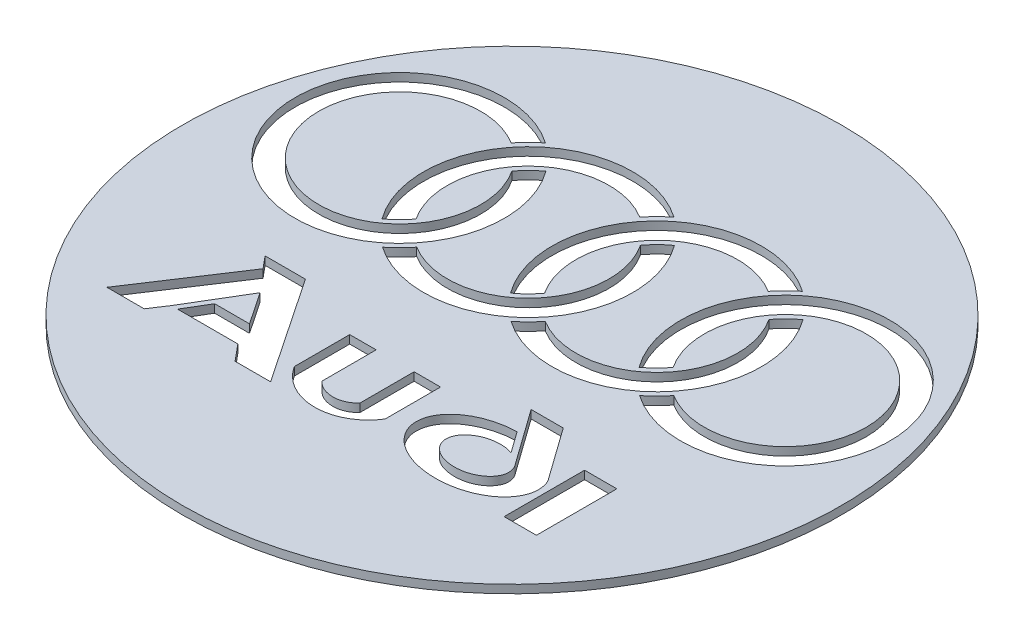
SolidWorks part; units mm, degrees
ref_plane "Front Plane" through (0, 0, 0) normal (0, 0, 1) x (1, 0, 0)
ref_plane "Top Plane" through (0, 0, 0) normal (0, 1, 0) x (1, 0, 0)
ref_plane "Right Plane" through (0, 0, 0) normal (1, 0, 0) x (0, 0, -1)
sketch "Sketch1" plane through (0, 0, 0) normal (0, 1, 0) x (1, 0, 0)
  circle A0 centre (0, 0) radius 127
  dimension "D1" = 254
extrude "Boss-Extrude1" add sketch "Sketch1" along normal blind 3.175
sketch "Sketch2" plane through (0, 3.175, 0) normal (0, 1, 0) x (1, 0, 0)
  line L0 (-62.6808, 3.9651) -> (137.3192, 3.9651) construction
  line L1 (-67.3927, -27.7613) -> (-63.4978, -32.4496)
  line L2 (-63.4978, -32.4496) -> (-87.3925, -68.7244)
  line L3 (-87.3925, -68.7244) -> (-73.0256, -68.7244)
  line L4 (-73.0256, -68.7244) -> (-68.8589, -62.399)
  line L5 (-66.4907, -62.399) -> (-43.2468, -62.399)
  line L6 (-43.2468, -62.399) -> (-37.9919, -68.7244)
  line L7 (-37.9919, -68.7244) -> (-24.3085, -68.7244)
  line L8 (-24.3085, -68.7244) -> (-51.8466, -27.7613)
  line L9 (-51.8466, -27.7613) -> (-67.3927, -27.7613)
  line L10 (-63.4978, -53.4431) -> (-56.0529, -41.0353)
  line L11 (-56.0529, -41.0353) -> (-47.7115, -53.4431)
  line L12 (-47.7115, -53.4431) -> (-61.1295, -53.4431)
  line L13 (35.1296, -27.7613) -> (47.5132, -27.7613)
  line L14 (47.5132, -27.7613) -> (62.2282, -48.3786)
  line L15 (35.1296, -27.7613) -> (50.6169, -49.4607)
  line L16 (-24.8134, -37.7244) -> (-14.6292, -37.7244)
  line L17 (65.691, -37.7244) -> (78.1298, -37.7244)
  line L18 (65.691, -37.7244) -> (65.691, -68.7244)
  line L19 (65.691, -68.7244) -> (78.1298, -68.7244)
  line L20 (78.1298, -37.7244) -> (78.1298, -68.7244)
  line L21 (10.1842, -37.7244) -> (10.1842, -59.0745)
  line L22 (0, -37.7244) -> (0, -58.6653)
  line L23 (-14.6292, -37.7244) -> (-14.6292, -58.6653)
  line L24 (-24.8134, -37.7244) -> (-24.8134, -59.0745)
  line L25 (0, -37.7244) -> (10.1842, -37.7244)
  line L26 (-68.8589, -62.399) -> (-63.4978, -53.4431)
  line L27 (-66.4907, -62.399) -> (-61.1295, -53.4431)
  line L28 (-67.1155, -63.4427) -> (-61.7543, -54.4868) construction
  line L31 (39.8509, -37.8742) -> (45.6791, -46.0402)
  line L32 (-24.3085, -68.7244) -> (84.4236, -68.7244) construction
  arc A0 (-24.8134, -59.0745) -> (10.1842, -59.0745) centre (-7.3146, -48.0336) ccw
  arc A1 (-14.6292, -58.6653) -> (0, -58.6653) centre (-7.3146, -51.6147) ccw
  arc A2 (-51.0647, 63.9504) -> (-42.7697, 5.4957) centre (-74.1332, 30.861) ccw
  arc A3 (-57.6633, 57.3592) -> (-49.3682, 11.8844) centre (-74.1332, 30.861) ccw
  arc A4 (-42.7697, 56.2262) -> (-50.6065, 13.6202) centre (-24.6032, 30.861) ccw
  arc A5 (-49.3682, 62.7006) -> (-57.205, 7.1083) centre (-24.6032, 30.861) ccw
  arc A6 (6.7603, 56.2262) -> (-1.0765, 13.6202) centre (24.9268, 30.861) ccw
  arc A7 (0.1618, 62.7006) -> (-7.675, 7.1083) centre (24.9268, 30.861) ccw
  arc A8 (56.2903, 56.2262) -> (48.4535, 13.6202) centre (74.4568, 30.861) ccw
  arc A9 (49.6918, 62.7006) -> (41.855, 7.1083) centre (74.4568, 30.861) ccw
  arc A10 (-41.0732, 4.3627) -> (0.1618, 11.8844) centre (-24.6032, 30.861) ccw
  arc A11 (-47.6717, -2.2285) -> (6.7603, 5.4957) centre (-24.6032, 30.861) ccw
  arc A12 (-49.3682, 11.8844) -> (-48.1299, 48.1017) centre (-74.1332, 30.861) ccw
  arc A13 (-42.7697, 5.4957) -> (-41.5314, 54.6136) centre (-74.1332, 30.861) ccw
  arc A14 (-1.5347, 63.9504) -> (-49.3682, 62.7006) centre (-24.6032, 30.861) ccw
  arc A15 (-8.1333, 57.3592) -> (-42.7697, 56.2262) centre (-24.6032, 30.861) ccw
  arc A16 (8.4568, 4.3627) -> (49.6918, 11.8844) centre (24.9268, 30.861) ccw
  arc A17 (1.8583, -2.2285) -> (56.2903, 5.4957) centre (24.9268, 30.861) ccw
  arc A18 (0.1618, 11.8844) -> (1.4001, 48.1017) centre (-24.6032, 30.861) ccw
  arc A19 (6.7603, 5.4957) -> (7.9986, 54.6136) centre (-24.6032, 30.861) ccw
  arc A20 (57.9868, 4.3627) -> (56.2903, 56.2262) centre (74.4568, 30.861) ccw
  arc A21 (51.3883, -2.2285) -> (49.6918, 62.7006) centre (74.4568, 30.861) ccw
  arc A22 (49.6918, 11.8844) -> (50.9301, 48.1017) centre (24.9268, 30.861) ccw
  arc A23 (56.2903, 5.4957) -> (57.5286, 54.6136) centre (24.9268, 30.861) ccw
  arc A24 (47.9953, 63.9504) -> (0.1618, 62.7006) centre (24.9268, 30.861) ccw
  arc A25 (41.3967, 57.3592) -> (6.7603, 56.2262) centre (24.9268, 30.861) ccw
  arc A26 (-47.6717, -2.2285) -> (-41.0732, 4.3627) centre (-74.1332, 30.861) ccw
  arc A27 (-48.1207, 64.3045) -> (-41.1897, 4.2179) centre (-74.1332, 30.861) ccw construction
  arc A28 (-57.1499, 54.5742) -> (-57.205, 54.6136) centre (-74.1332, 30.861) ccw
  arc A29 (-57.1499, 54.5742) -> (-50.9811, 13.1203) centre (-74.1332, 30.861) ccw construction
  arc A30 (-57.205, 7.1083) -> (-50.6065, 13.6202) centre (-74.1332, 30.861) ccw
  arc A31 (-41.5314, 54.6136) -> (-48.1299, 48.1017) centre (-24.6032, 30.861) ccw
  arc A32 (-57.6633, 4.3627) -> (-48.1299, 13.6202) centre (-74.1332, 30.861) ccw
  arc A33 (-51.0647, 63.9504) -> (-57.6633, 57.3592) centre (-24.6032, 30.861) ccw
  arc A34 (-41.5865, 54.5742) -> (-48.1299, 13.6202) centre (-24.6032, 30.861) ccw construction
  arc A35 (-49.3682, 62.7006) -> (-42.7697, 5.4957) centre (-74.1332, 30.861) ccw construction
  arc A36 (-55.9667, 56.2262) -> (-49.3682, 11.8844) centre (-74.1332, 30.861) ccw construction
  arc A37 (-50.6158, 64.3045) -> (-57.6633, 4.3627) centre (-24.6032, 30.861) ccw construction
  arc A38 (-1.5347, 63.9504) -> (-8.1333, 57.3592) centre (24.9268, 30.861) ccw
  arc A39 (-7.675, 7.1083) -> (-1.0765, 13.6202) centre (-24.6032, 30.861) ccw
  arc A40 (1.8583, -2.2285) -> (8.4568, 4.3627) centre (-24.6032, 30.861) ccw
  arc A41 (7.9986, 54.6136) -> (1.4001, 48.1017) centre (24.9268, 30.861) ccw
  arc A42 (-1.0858, 64.3045) -> (-1.0858, -2.5826) centre (24.9268, 30.861) ccw construction
  arc A43 (7.9435, 54.5742) -> (7.9435, 7.1477) centre (24.9268, 30.861) ccw construction
  arc A44 (6.7603, 56.2262) -> (6.7603, 5.4957) centre (24.9268, 30.861) ccw construction
  arc A45 (0.1618, 62.7006) -> (0.1618, -0.9787) centre (24.9268, 30.861) ccw construction
  arc A46 (41.9101, 54.5742) -> (7.9435, 54.5742) centre (24.9268, 30.861) ccw construction
  arc A47 (48.0789, 13.1203) -> (41.9101, 54.5742) centre (24.9268, 30.861) ccw construction
  arc A48 (-48.8338, -3.8954) -> (8.3403, 4.2179) centre (-24.6032, 30.861) ccw construction
  arc A49 (-40.0005, 6.0885) -> (-1.4511, 13.1203) centre (-24.6032, 30.861) ccw construction
  arc A50 (41.855, 7.1083) -> (48.4535, 13.6202) centre (24.9268, 30.861) ccw
  arc A51 (51.3883, -2.2285) -> (57.9868, 4.3627) centre (24.9268, 30.861) ccw
  arc A52 (47.9953, 63.9504) -> (41.3967, 57.3592) centre (74.4568, 30.861) ccw
  arc A53 (57.5286, 54.6136) -> (50.9301, 48.1017) centre (74.4568, 30.861) ccw
  arc A54 (-7.675, 7.1083) -> (-1.0765, 13.6202) centre (-24.6032, 30.861) ccw
  arc A55 (1.8583, -2.2285) -> (8.4568, 4.3627) centre (-24.6032, 30.861) ccw
  arc A57 (-1.5347, 63.9504) -> (-8.1333, 57.3592) centre (24.9268, 30.861) ccw
  arc A58 (43.0933, 56.2262) -> (6.7603, 56.2262) centre (24.9268, 30.861) ccw construction
  arc A59 (49.6918, 11.8844) -> (43.0933, 56.2262) centre (24.9268, 30.861) ccw construction
  arc A60 (7.9986, 54.6136) -> (1.4001, 48.1017) centre (24.9268, 30.861) ccw [skipped]
  ellipse E0 centre (40.1787, -53.5123) end of major axis (51.7852, -52.5581) minor radius 8.2102 (45.6791, -46.0402) -> (50.6169, -49.4607) ccw
  ellipse E1 centre (40.1787, -53.5123) end of major axis (63.32, -52.7892) minor radius 15.6411 (39.8509, -37.8742) -> (62.2282, -48.3786) ccw
  dimension "D2" = 2.032
  dimension "D4" = 2.032
  dimension "D5" = 2.032
  dimension "D6" = 2.032
  dimension "D7" = 2.032
  dimension "D8" = 2.032
  dimension "D9" = 2.032
  dimension "D10" = 2.032
  dimension "D1" = 4
  dimension "D11" = 2
extrude "Cut-Extrude1" cut sketch "Sketch2" against normal blind 3.175
